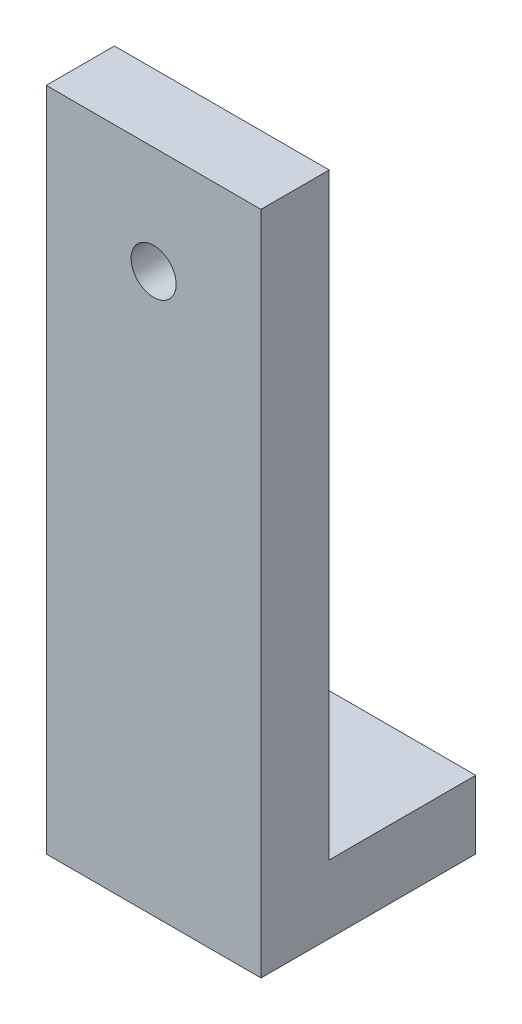
SolidWorks part; units mm, degrees
material "6061-T6 (SS)"
ref_plane "Front Plane" through (0, 0, 0) normal (0, 0, 1) x (1, 0, 0)
ref_plane "Top Plane" through (0, 0, 0) normal (0, 1, 0) x (1, 0, 0)
ref_plane "Right Plane" through (0, 0, 0) normal (1, 0, 0) x (0, 0, -1)
sketch "Sketch1" plane through (0, 0, 0) normal (1, 0, 0) x (0, 0, -1)
  line L0 (0, 0) -> (0, 62)
  line L1 (0, 62) -> (6.35, 62)
  line L2 (6.35, 62) -> (6.35, 6.35)
  line L3 (6.35, 6.35) -> (20, 6.35)
  line L4 (20, 6.35) -> (20, 0)
  line L5 (20, 0) -> (0, 0)
  dimension "D1" = 6.35
  dimension "D2" = 20
  dimension "D3" = 62
extrude "Boss-Extrude1" add sketch "Sketch1" along normal blind 20
hole_wizard "M5 Tapped Hole1" positions "Sketch3" profile "Sketch4" tap size "M5" standard "ISO" end condition through all
sketch "Sketch3" plane through (0, 0, 0) normal (0, 0, 1) x (1, 0, 0)
  line L0 (20, 62) -> (0, 62) construction
  line L1 (10, 62) -> (10, 0) construction
  line L2 (20, 0) -> (0, 0) construction
  point P0 (10, 52)
  dimension "D1" = 10
sketch "Sketch4" plane through (10, 52, 0) normal (1, 0, 0) x (0, -1, 0)
  line L0 (0, 0) -> (0, 20)
  line L1 (0, 20) -> (2.1, 20)
  line L2 (2.1, 20) -> (2.1, 0)
  line L5 (2.1, 0) -> (0, 0)
  line L11 (0, -6.35) -> (0, 107.95) construction
  dimension "Thru Tap Drill Dia." = 4.2
  dimension "Thru Tap Drill Depth" = 20
cosmetic thread "Hole Thread1"
